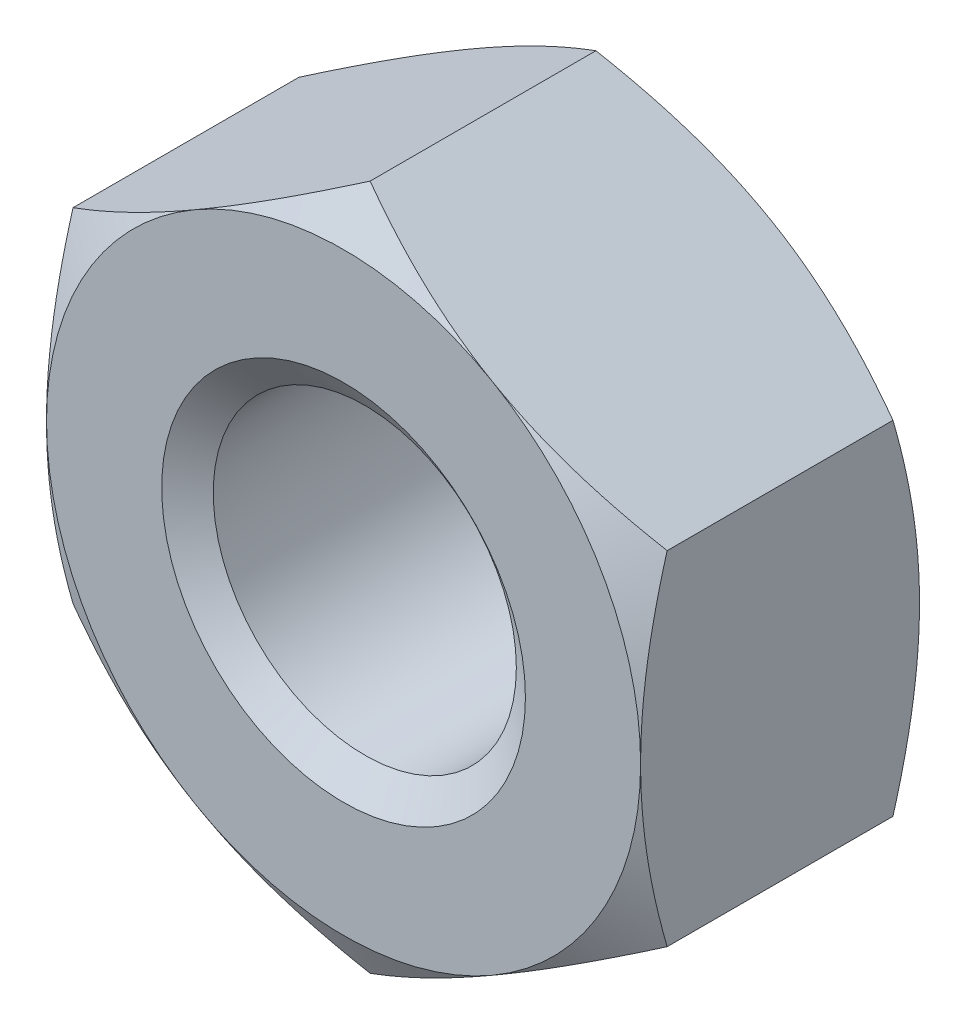
SolidWorks part; units mm, degrees
ref_plane "Plane1" through (0, 0, 0) normal (0, 0, 1) x (1, 0, 0)
ref_plane "Plane2" through (0, 0, 0) normal (0, 1, 0) x (1, 0, 0)
ref_plane "Plane3" through (0, 0, 0) normal (1, 0, 0) x (0, 0, -1)
sketch "BaseNutSke" plane through (0, 0, 0) normal (0, 0, 1) x (1, 0, 0)
  line L6 (2.45, 1.4145) -> (2.45, -1.4145)
  line L7 (-2.45, 1.4145) -> (-2.45, -1.4145)
  line L8 (2.45, 1.4145) -> (0, 2.829)
  line L9 (0, 2.829) -> (-2.45, 1.4145)
  line L10 (-2.45, -1.4145) -> (0, -2.829)
  line L11 (0, -2.829) -> (2.45, -1.4145)
  circle A0 centre (0, 0) radius 1.25
  dimension "D4" = 2.45
  dimension "Tap_drill" = 2.5
  dimension "D1" = 120
  dimension "D2" = 2.45
  dimension "D3" = 2.45
  dimension "Width_flats" = 4.9
extrude "BaseNut" add sketch "BaseNutSke" against normal blind 2.3
cosmetic thread "ThreadCosmetic"
sketch "Sketch4" plane through (0, 0, 0) normal (1, 0, 0) x (0, 0, -1)
  line L0 (2.3, 2.45) -> (2.29, 2.45)
  line L1 (2.3, 2.45) -> (2.3, 12.829)
  line L2 (2.29, 12.829) -> (2.3, 12.829)
  line L3 (2.29, 12.829) -> (2.29, 2.45)
  line L4 (0, 0) -> (34.925, 0) construction
  line L6 (2.3, 1.4145) -> (2.3, 2.829) construction
  line L7 (0, 2.45) -> (-10, 2.45)
  line L8 (0, 1.4145) -> (0, 2.829) construction
  line L9 (0.2188, 2.829) -> (0.2188, 12.829)
  line L10 (0.2188, 12.829) -> (-10, 12.829)
  line L11 (-10, 12.829) -> (-10, 2.45)
  line L12 (0, 2.45) -> (0.2188, 2.829)
  line L14 (0, 1.4145) -> (0, -1.4145) construction
  line L15 (2.3, 2.829) -> (0, 2.829) construction
  dimension "D1" = 2.45
  dimension "D2" = 30
  dimension "Bearing_ht" = 0.01
  dimension "D3" = 10
  dimension "D4" = 10
revolve "Bearing-Face" [suppressed] cut sketch "Sketch4" angle 360 about L4
sketch "Sketch3" plane through (0, 0, 0) normal (1, 0, 0) x (0, 0, -1)
  line L0 (2.3, 2.45) -> (2.0812, 2.829)
  line L1 (2.0812, 2.829) -> (2.0812, 12.829)
  line L2 (2.0812, 12.829) -> (12.3, 12.829)
  line L3 (12.3, 12.829) -> (12.3, 2.45)
  line L4 (12.3, 2.45) -> (2.3, 2.45)
  line L5 (2.3, 1.4145) -> (2.3, 2.829) construction
  line L6 (2.3, 2.829) -> (0, 2.829) construction
  line L7 (0, 0) -> (38.6776, 0) construction
  line L8 (2.3, 0) -> (0, 0) construction
  line L9 (1.15, 2.829) -> (1.15, 44.222) construction
  line L10 (0.2188, 12.829) -> (-10, 12.829)
  line L11 (-10, 12.829) -> (-10, 2.45)
  line L12 (-10, 2.45) -> (0, 2.45)
  line L13 (0, 2.45) -> (0.2188, 2.829)
  line L14 (0.2188, 2.829) -> (0.2188, 12.829)
  line L16 (2.3, 2.829) -> (0, 2.829) construction
  dimension "D1" = 2.45
  dimension "D2" = 30
  dimension "D3" = 10
  dimension "D4" = 10
revolve "Double-Chamfer" cut sketch "Sketch3" angle 360 about L7
sketch "Sketch5"
  line L0 (2.2746, 1.5) -> (2.082, 1.225)
  line L1 (2.3254, 1.5) -> (2.2746, 1.5)
  line L2 (2.3254, 1.5) -> (2.3254, 1.225)
  line L3 (2.3254, 1.225) -> (2.082, 1.225)
  line L6 (-0.0508, 1.5) -> (0, 1.5)
  line L7 (0, 1.5) -> (0.1926, 1.225)
  line L9 (0.1926, 1.225) -> (-0.0508, 1.225)
  line L10 (-0.0508, 1.225) -> (-0.0508, 1.5)
  line L11 (25.0375, 0) -> (38.388, 0) construction
  line L12 (2.3, 0) -> (0, 0) construction
pattern_linear "ThdSchPat" [suppressed]
revolve "ThreadSchematic" cut sketch "ThdSchSke"
sketch "ThdSchSke" plane through (0, 0, 0) normal (0, 1, 0) x (1, 0, 0)
  line L0 (-1.5, 0.0254) -> (-1.25, 0.2005)
  line L1 (-1.25, 0.2005) -> (-0.625, 0.2005)
  line L2 (-0.625, 0.2005) -> (-0.625, -0.1497)
  line L3 (-0.625, -0.1497) -> (-1.25, -0.1497)
  line L4 (-1.25, -0.1497) -> (-1.5, 0.0254)
  line L5 (-3.175, 0.5) -> (3.175, 0.5) construction
  line L6 (0, 0.5) -> (0, -2.9874) construction
  line L7 (0, 2.0995) -> (0, 0.1751) construction
  dimension "D1" = 35
  dimension "VeeAngle" = 70
  dimension "SideAngle" = 55
  dimension "D2" = 0.0508
  dimension "OverCut" = 1.25
  dimension "Tap_Drill" = 2.5
  dimension "Advance" = 0.4498
  dimension "Thread_major" = 3
  dimension "Num_threads" = 6
  dimension "D4" = 50
  dimension "Offset1" = 2.3254
  dimension "ThreadMajor" = 1.5
  dimension "ChamferDepth" = 0.275
  dimension "Offset2" = 2.3762
revolve "EndChamfer" cut sketch "Sketch5" angle 360 about L11
equation "\"D2@BaseNutSke\" = \"Width_flats@BaseNutSke\" / 2"
equation "\"D3@BaseNutSke\" = \"Width_flats@BaseNutSke\" / 2"
equation "\"D1@Sketch3\" = \"Width_flats@BaseNutSke\" /2"
equation "\"D1@Sketch4\" = \"D2@BaseNutSke\""
equation "\"D4@BaseNutSke\" = \"D3@BaseNutSke\""
equation "\"Thread_major@ThdSchSke\" = \"Thread_major@ThreadCosmetic\""
equation "\"Tap_drill@ThdSchSke\" = \"Tap_drill@BaseNutSke\""
equation "\"Overcut@ThdSchSke\" = \"Tap_drill@ThdSchSke\" * 0.5"
equation "\"Num_threads@ThdSchPat\" = int(  ( \"Thickness@BaseNut\" - 0.0508 ) / \"Advance@ThdSchSke\" + 0.999 )  + 1"
equation "\"Advance@ThdSchPat\" = ( \"Thickness@BaseNut\" - 0.0508 ) /  (\"Num_threads@ThdSchPat\" - 1) 'relax it"
equation "' \"Num_threads@ThdSchPat\" = \"Num_threads@ThdSchPat\" - sgn( \"Num_threads@ThdSchPat\" - 1) '---chamfered tips only---"
equation "\"ThreadMajor@Sketch5\" = \"Thread_major@ThreadCosmetic\" * 0.5"
equation "\"ChamferDepth@Sketch5\" = (\"Thread_major@ThreadCosmetic\" - \"Tap_drill@BaseNutSke\") * 0.55"
equation "\"Offset1@Sketch5\" = \"Thickness@BaseNut\" + 0.0254"
equation "\"Offset2@Sketch5\" = \"Offset1@Sketch5\" + 0.0508"
